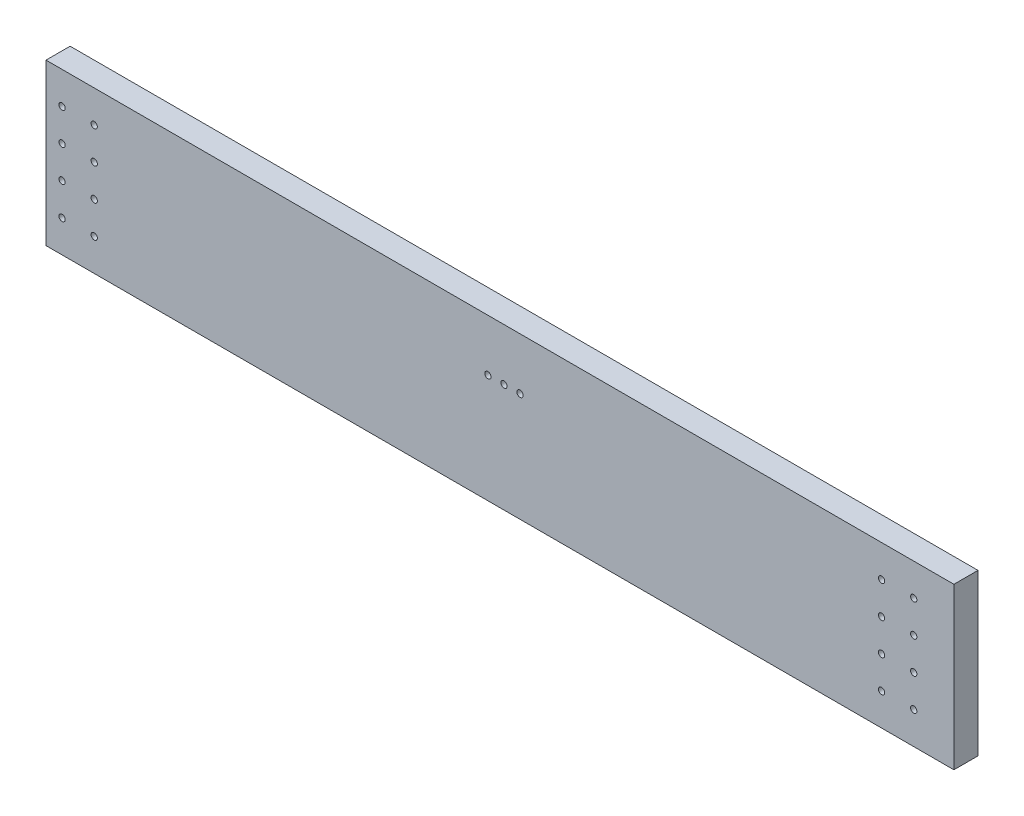
SolidWorks part; units mm, degrees
material "Pine"
ref_plane "Front Plane" through (0, 0, 0) normal (0, 0, 1) x (1, 0, 0)
ref_plane "Top Plane" through (0, 0, 0) normal (0, 1, 0) x (1, 0, 0)
ref_plane "Right Plane" through (0, 0, 0) normal (1, 0, 0) x (0, 0, -1)
sketch "Sketch1" plane through (0, 0, 0) normal (0, 0, 1) x (1, 0, 0)
  line L1 (0, 0) -> (717.55, 0)
  line L2 (0, 0) -> (0, 127)
  line L3 (0, 127) -> (717.55, 127)
  line L4 (717.55, 0) -> (717.55, 127)
  line L6 (717.55, 0) -> (717.55, 127)
  line L9 (0, 127) -> (-19.05, 127)
  line L10 (0, 127) -> (0, 0)
  line L11 (0, 0) -> (-19.05, 0)
  line L12 (-19.05, 127) -> (-19.05, 0)
  dimension "D1" = 717.55
  dimension "D2" = 127
  dimension "D3" = 19.05
extrude "Boss-Extrude1" add sketch "Sketch1" along normal blind 19.05 contours L1 L4 L3 L2
sketch "Sketch2" plane through (0, 0, 19.05) normal (0, 0, 1) x (1, 0, 0)
  line L3 (0, 0) -> (0, 127) construction
  line L4 (0, 127) -> (717.55, 127) construction
  line L5 (717.55, 0) -> (717.55, 127) construction
  circle A0 centre (12.7, 101.6) radius 2.4892
  circle A1 centre (38.1, 101.6) radius 2.4892
  circle A2 centre (38.1, 76.2) radius 2.4892
  circle A3 centre (38.1, 50.8) radius 2.4892
  circle A4 centre (38.1, 25.4) radius 2.4892
  circle A5 centre (12.7, 76.2) radius 2.4892
  circle A6 centre (12.7, 50.8) radius 2.4892
  circle A7 centre (12.7, 25.4) radius 2.4892
  circle A8 centre (685.8, 101.6) radius 2.4892
  circle A9 centre (660.4, 101.6) radius 2.4892
  circle A10 centre (660.4, 76.2) radius 2.4892
  circle A11 centre (660.4, 50.8) radius 2.4892
  circle A12 centre (660.4, 25.4) radius 2.4892
  circle A13 centre (685.8, 76.2) radius 2.4892
  circle A14 centre (685.8, 50.8) radius 2.4892
  circle A15 centre (685.8, 25.4) radius 2.4892
  dimension "D1" = 4.9784
  dimension "D2" = 25.4
  dimension "D3" = 12.7
  dimension "D6" = 25.4
  dimension "D7" = 31.75
  dimension "D8" = 4.9784
  dimension "D11" = 25.4
  dimension "D12" = 25.4
  dimension "D13" = 25.4
  dimension "D14" = 25.4
  dimension "D4" = 2
  dimension "D5" = 4
  dimension "D9" = 2
  dimension "D10" = 4
extrude "Cut-Extrude1" cut sketch "Sketch2" against normal blind 25.4
sketch "Sketch4" plane through (0, 0, 19.05) normal (0, 0, 1) x (1, 0, 0)
  line L0 (349.25, 85.979) -> (374.65, 85.979) construction
  line L1 (0, 127) -> (717.55, 127) construction
  line L2 (0, 0) -> (0, 127) construction
  circle A0 centre (349.25, 85.979) radius 2.4892
  circle A1 centre (361.95, 85.979) radius 2.4892
  circle A2 centre (374.65, 85.979) radius 2.4892
  dimension "D1" = 4.9784
  dimension "D2" = 41.021
  dimension "D4" = 374.65
  dimension "D3" = 12.7
extrude "Cut-Extrude2" cut sketch "Sketch4" against normal through all
